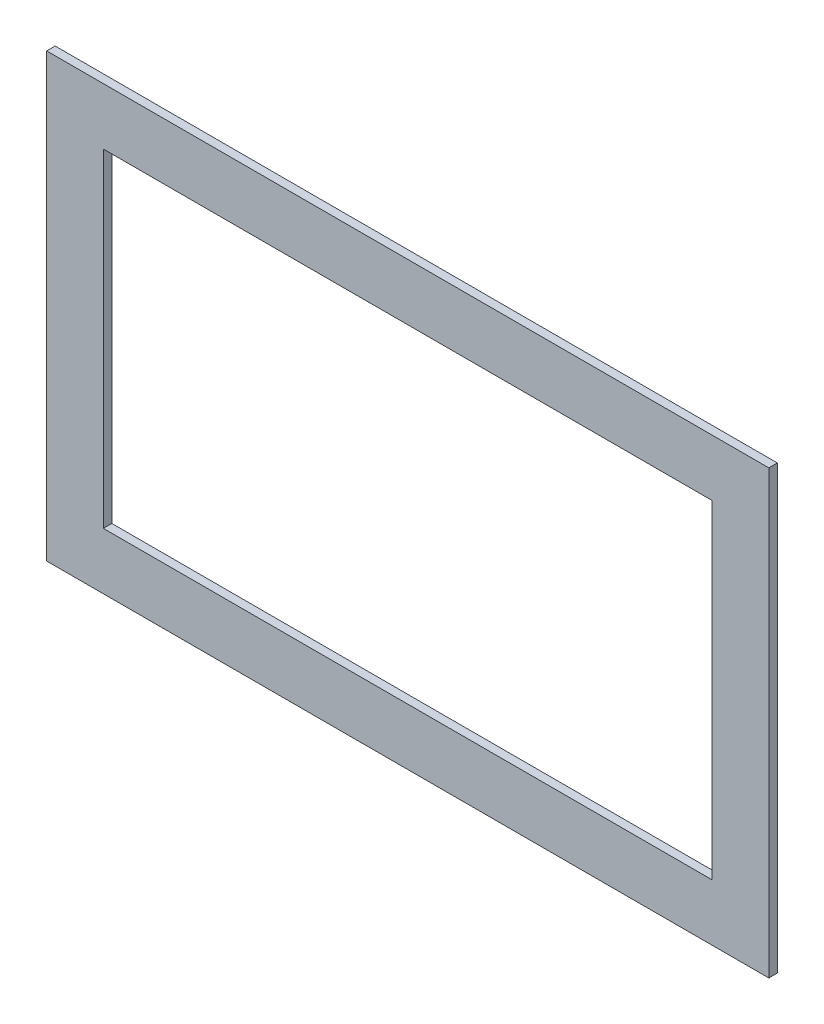
SolidWorks part; units mm, degrees
ref_plane "Front Plane" through (0, 0, 0) normal (0, 0, 1) x (1, 0, 0)
ref_plane "Top Plane" through (0, 0, 0) normal (0, 1, 0) x (1, 0, 0)
ref_plane "Right Plane" through (0, 0, 0) normal (1, 0, 0) x (0, 0, -1)
ref_plane "Plane1" through (0, 0, 24.2899) normal (0, 0, -1) x (-1, 0, 0)
sketch "Sketch2" plane through (0, 0, 24.2899) normal (0, 0, -1) x (-1, 0, 0)
  line L1 (-9.7825, 156.5857) -> (245.2175, 156.5857)
  line L2 (-9.7825, 156.5857) -> (-9.7825, 0.5857)
  line L3 (-9.7825, 0.5857) -> (245.2175, 0.5857)
  line L4 (245.2175, 156.5857) -> (245.2175, 0.5857)
  line L6 (10.2175, 136.5857) -> (225.2175, 136.5857)
  line L7 (10.2175, 136.5857) -> (10.2175, 20.5857)
  line L8 (10.2175, 20.5857) -> (225.2175, 20.5857)
  line L9 (225.2175, 136.5857) -> (225.2175, 20.5857)
  dimension "D1" = 255
  dimension "D2" = 156
  dimension "D3" = 20
  dimension "D4" = 20
  dimension "D5" = 20
  dimension "D6" = 20
extrude "Boss-Extrude1" add sketch "Sketch2" along normal blind 3
